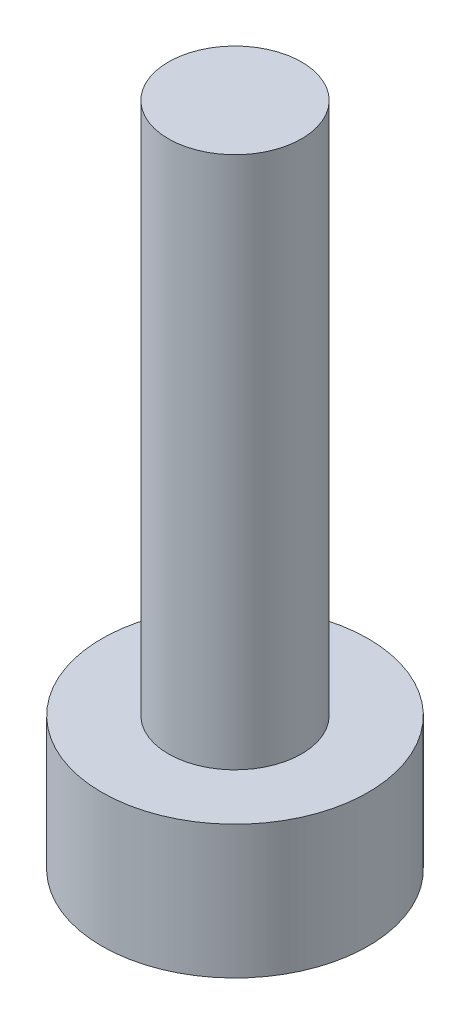
SolidWorks part; units mm, degrees
ref_plane "Front Plane" through (0, 0, 0) normal (0, 0, 1) x (1, 0, 0)
ref_plane "Top Plane" through (0, 0, 0) normal (0, 1, 0) x (1, 0, 0)
ref_plane "Right Plane" through (0, 0, 0) normal (1, 0, 0) x (0, 0, -1)
sketch "Sketch1" plane through (0, 0, 0) normal (0, 1, 0) x (1, 0, 0)
  circle A0 centre (0, 0) radius 3
  dimension "D1" = 6
extrude "Boss-Extrude1" add sketch "Sketch1" along normal blind 3
sketch "Sketch2" plane through (0, 3, 0) normal (0, 1, 0) x (1, 0, 0)
  circle A0 centre (0, 0) radius 1.5
  dimension "D1" = 3
extrude "Boss-Extrude2" add sketch "Sketch2" along normal blind 12
